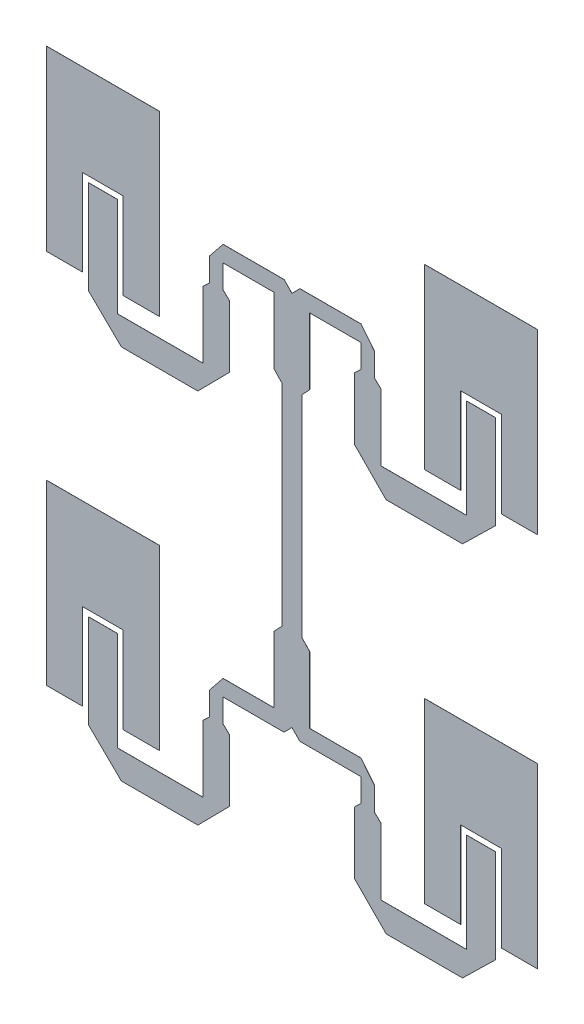
SolidWorks part; units mm, degrees
material "Медь"
ref_plane "Спереди" through (0, 0, 0) normal (0, 0, 1) x (1, 0, 0)
ref_plane "Сверху" through (0, 0, 0) normal (0, 1, 0) x (1, 0, 0)
ref_plane "Справа" through (0, 0, 0) normal (1, 0, 0) x (0, 0, -1)
sketch "Patch1" plane through (0, 0, 0) normal (0, 0, 1) x (1, 0, 0)
  line L0 (0, 0) -> (0, 64.0927) construction
  line L1 (-59.6963, 67.2973) -> (-32.2263, 67.2973)
  line L2 (-59.6963, 67.2973) -> (-59.6964, 24.0919)
  line L3 (-59.6964, 24.0919) -> (-50.8953, 24.0919)
  line L4 (-32.2263, 67.2973) -> (-32.2263, 24.0919)
  line L5 (-59.6963, 67.2973) -> (-32.2263, 24.0919) construction
  line L6 (-59.6964, 24.0919) -> (-32.2263, 67.2973) construction
  line L7 (-45.9613, 45.6946) -> (-45.9613, 25.1206) construction
  line L8 (45.9613, 45.6946) -> (45.9613, 25.1206) construction
  line L9 (-50.8953, 24.0919) -> (-50.8952, 45.0723)
  line L10 (-50.8952, 45.0723) -> (-41.0273, 45.0723)
  line L11 (-41.0273, 24.0919) -> (-41.0273, 45.0723)
  line L12 (-41.0273, 24.0919) -> (-32.2263, 24.0919)
  line L13 (59.6964, 24.0919) -> (32.2263, 67.2973) construction
  line L14 (59.6963, 67.2973) -> (32.2263, 24.0919) construction
  line L15 (41.0273, 24.0919) -> (32.2263, 24.0919)
  line L16 (41.0273, 24.0919) -> (41.0273, 45.0723)
  line L17 (50.8952, 45.0723) -> (41.0273, 45.0723)
  line L18 (50.8953, 24.0919) -> (50.8952, 45.0723)
  line L19 (32.2263, 67.2973) -> (32.2263, 24.0919)
  line L20 (59.6964, 24.0919) -> (50.8953, 24.0919)
  line L21 (59.6963, 67.2973) -> (59.6964, 24.0919)
  line L22 (59.6963, 67.2973) -> (32.2263, 67.2973)
  line L23 (-41.0274, -67.2973) -> (-32.2263, -67.2973)
  line L24 (-32.2263, -24.0919) -> (-32.2263, -67.2973)
  line L25 (-59.6964, -24.0919) -> (-32.2263, -24.0919)
  line L26 (-59.6964, -24.0919) -> (-32.2263, -67.2973) construction
  line L27 (-50.8953, -46.3169) -> (-41.0274, -46.3169)
  line L28 (-59.6964, -24.0919) -> (-59.6964, -67.2973)
  line L29 (-50.8953, -67.2973) -> (-50.8953, -46.3169)
  line L30 (-59.6964, -67.2973) -> (-32.2263, -24.0919) construction
  line L31 (-41.0274, -67.2973) -> (-41.0274, -46.3169)
  line L32 (-59.6964, -67.2973) -> (-50.8953, -67.2973)
  line L33 (-45.9613, -45.6946) -> (-45.9613, -66.2686) construction
  line L34 (45.9613, -45.6946) -> (45.9613, -66.2686) construction
  line L35 (59.6964, -67.2973) -> (32.2263, -24.0919) construction
  line L36 (59.6964, -24.0919) -> (32.2263, -67.2973) construction
  line L37 (59.6964, -67.2973) -> (50.8953, -67.2973)
  line L38 (41.0274, -67.2973) -> (41.0274, -46.3169)
  line L39 (50.8953, -67.2973) -> (50.8953, -46.3169)
  line L40 (59.6964, -24.0919) -> (59.6964, -67.2973)
  line L41 (50.8953, -46.3169) -> (41.0274, -46.3169)
  line L42 (59.6964, -24.0919) -> (32.2263, -24.0919)
  line L43 (32.2263, -24.0919) -> (32.2263, -67.2973)
  line L44 (41.0274, -67.2973) -> (32.2263, -67.2973)
  point P0 (-45.9613, 45.6946)
  point P24 (-45.9613, -45.6946)
  dimension "D1" = 43.2054
  dimension "D2" = 27.4701
  dimension "D3" = 45.9613
  dimension "D5" = 20.9804
  dimension "D6" = 8.8011
  dimension "D4" = 45.6946
  dimension "D7" = 43.2054
  dimension "D8" = 27.4701
  dimension "D9" = 20.9804
  dimension "D10" = 8.8011
  dimension "D11" = 45.9613
  dimension "D12" = 45.6946
sketch "Feed1" plane through (0, 0, 0) normal (0, 0, 1) x (1, 0, 0)
  line L0 (-50.8952, 45.0723) -> (-41.0273, 45.0723) construction
  line L1 (-49.4729, 43.6499) -> (-42.4498, 43.6499)
  line L2 (-49.4729, 43.6499) -> (-49.4729, 20.8915)
  line L3 (-49.4729, 20.8915) -> (-41.4719, 13.0683)
  line L4 (-42.4498, 43.6499) -> (-42.4498, 19.558)
  line L5 (-50.8953, 24.0919) -> (-50.8953, 45.0723) construction
  line L6 (-15.1575, 20.8915) -> (-22.8918, 13.0683)
  line L7 (-21.6472, 35.7378) -> (-20.047, 37.2491)
  line L8 (15.1574, -70.4977) -> (15.1574, -55.4736)
  line L9 (-41.4719, 13.0683) -> (-22.8918, 13.0683)
  line L10 (-21.6472, 19.558) -> (-21.6472, 35.7378)
  line L11 (1.9114, 47.0281) -> (0, 45.0723)
  line L12 (42.4498, -71.8312) -> (21.6471, -71.8312)
  line L13 (-20.047, 42.9387) -> (-20.047, 37.2491)
  line L14 (41.4718, -78.3209) -> (22.8917, -78.3209)
  line L15 (-42.4498, 19.558) -> (-21.6472, 19.558)
  line L16 (-15.1574, -70.4977) -> (-22.8917, -78.3209)
  line L17 (-20.047, 42.9387) -> (-16.7577, 47.0281)
  line L18 (-15.1575, 20.8915) -> (-15.1575, 35.9156)
  line L19 (-16.7577, 43.1165) -> (-4.3117, 43.1165)
  line L20 (-16.7577, 43.1165) -> (-16.7577, 37.4269)
  line L21 (-16.7577, 37.4269) -> (-15.1575, 35.9156)
  line L22 (0, 0) -> (0, 64.0927) construction
  line L23 (-16.7577, 47.0281) -> (-1.9114, 47.0281)
  line L24 (-21.6471, -55.6514) -> (-20.0469, -54.1401)
  line L25 (-16.7576, -48.2727) -> (-1.9114, -48.2727)
  line L26 (-1.9114, 47.0281) -> (0, 45.0723)
  line L27 (16.7577, 47.0281) -> (1.9114, 47.0281)
  line L28 (16.7577, 37.4269) -> (15.1575, 35.9156)
  line L29 (16.7577, 43.1165) -> (16.7577, 37.4269)
  line L30 (16.7577, 43.1165) -> (4.3117, 43.1165)
  line L31 (15.1575, 20.8915) -> (15.1575, 35.9156)
  line L32 (20.047, 42.9387) -> (16.7577, 47.0281)
  line L33 (-21.6471, -71.8312) -> (-21.6471, -55.6514)
  line L34 (42.4498, 19.558) -> (21.6472, 19.558)
  line L35 (-20.047, -48.4505) -> (-16.7577, -44.3611)
  line L36 (20.047, 42.9387) -> (20.047, 37.2491)
  line L37 (-49.4729, -47.7393) -> (-42.4498, -47.7393)
  line L38 (21.6472, 19.558) -> (21.6472, 35.7378)
  line L39 (41.4719, 13.0683) -> (22.8918, 13.0683)
  line L40 (21.6472, 35.7378) -> (20.047, 37.2491)
  line L41 (15.1575, 20.8915) -> (22.8918, 13.0683)
  line L42 (42.4498, 43.6499) -> (42.4498, 19.558)
  line L43 (49.4729, 20.8915) -> (41.4719, 13.0683)
  line L44 (49.4729, 43.6499) -> (49.4729, 20.8915)
  line L45 (49.4729, 43.6499) -> (42.4498, 43.6499)
  line L46 (-49.4729, -70.4977) -> (-41.4718, -78.3209)
  line L47 (20.047, -48.4505) -> (20.0469, -54.1401)
  line L48 (15.1574, -70.4977) -> (22.8917, -78.3209)
  line L49 (42.4498, -47.7393) -> (42.4498, -71.8312)
  line L50 (49.4729, -47.7393) -> (49.4729, -70.4977)
  line L51 (-4.3117, 26.9367) -> (-4.3117, 43.1165)
  line L52 (16.7576, -53.9623) -> (15.1574, -55.4736)
  line L53 (-42.4498, -47.7393) -> (-42.4498, -71.8312)
  line L54 (16.7577, -44.3611) -> (4.3117, -44.3611)
  line L55 (16.7576, -48.2727) -> (16.7576, -53.9623)
  line L56 (21.6471, -55.6514) -> (20.0469, -54.1401)
  line L57 (49.4729, -47.7393) -> (42.4498, -47.7393)
  line L58 (-49.4729, -47.7393) -> (-49.4729, -70.4977)
  line L59 (-16.7576, -53.9623) -> (-15.1574, -55.4736)
  line L60 (21.6471, -71.8312) -> (21.6471, -55.6514)
  line L61 (-42.4498, -71.8312) -> (-21.6471, -71.8312)
  line L62 (-16.7577, -44.3611) -> (-4.3117, -44.3611)
  line L63 (-41.4718, -78.3209) -> (-22.8917, -78.3209)
  line L64 (-16.7576, -48.2727) -> (-16.7576, -53.9623)
  line L65 (-15.1574, -70.4977) -> (-15.1574, -55.4736)
  line L66 (16.7576, -48.2727) -> (1.9114, -48.2727)
  line L67 (0, -86.952) -> (0, -22.8593) construction
  line L68 (49.4729, -70.4977) -> (41.4718, -78.3209)
  line L69 (4.3117, 26.9367) -> (4.3117, 43.1165)
  line L70 (-20.047, -48.4505) -> (-20.0469, -54.1401)
  line L71 (20.047, -48.4505) -> (16.7577, -44.3611)
  line L72 (-1.9114, -48.2727) -> (0, -46.3169)
  line L73 (1.9114, -48.2727) -> (0, -46.3169)
  line L74 (-4.3117, -44.3611) -> (-4.3117, -28.1813)
  line L75 (4.3117, -44.3611) -> (4.3117, -28.1813)
  line L76 (-2.4447, 24.9809) -> (-4.3117, 26.9367)
  line L77 (-50.8953, -46.3169) -> (-41.0274, -46.3169) construction
  line L78 (-41.0274, -67.2973) -> (-41.0274, -46.3169) construction
  line L79 (-4.3117, -28.1813) -> (-2.4447, -26.2255)
  line L80 (4.3117, -28.1813) -> (2.4447, -26.2255)
  line L81 (-2.4447, -26.2255) -> (-2.4447, 24.9809)
  line L82 (2.4447, -26.2255) -> (2.4447, 24.9809)
  line L83 (2.4447, 24.9809) -> (4.3117, 26.9367)
  dimension "D1" = 1.4224
  dimension "D2" = 1.4224
  dimension "D5" = 7.8232
  dimension "D6" = 8.001
  dimension "D7" = 22.7584
  dimension "D8" = 18.5801
  dimension "D11" = 7.7343
  dimension "D13" = 15.0241
  dimension "D14" = 3.2893
  dimension "D16" = 1.5113
  dimension "D17" = 1.6002
  dimension "D15" = 5.6896
  dimension "D18" = 1.5113
  dimension "D19" = 7.8232
  dimension "D23" = 5.6896
  dimension "D21" = 3.2893
  dimension "D22" = 3.9116
  dimension "D25" = 1.9558
  dimension "D24" = 14.8463
  dimension "D20" = 1.9114
  dimension "D10" = 16.1798
  dimension "D12" = 6.4897
  dimension "D9" = 6.4897
  dimension "D3" = 1.4224
  dimension "D4" = 7.8232
  dimension "D27" = 8.001
  dimension "D28" = 22.7584
  dimension "D29" = 18.5801
  dimension "D30" = 7.7343
  dimension "D31" = 15.0241
  dimension "D32" = 3.2893
  dimension "D33" = 1.5113
  dimension "D34" = 1.6002
  dimension "D35" = 5.6896
  dimension "D36" = 1.5113
  dimension "D37" = 7.8232
  dimension "D38" = 5.6896
  dimension "D39" = 3.2893
  dimension "D40" = 3.9116
  dimension "D45" = 16.1798
  dimension "D46" = 6.4897
  dimension "D47" = 6.4897
  dimension "D41" = 1.9558
  dimension "D42" = 4.3117
  dimension "D43" = 4.3117
  dimension "D44" = 1.4224
  dimension "D48" = 1.4224
  dimension "D49" = 1.4224
  dimension "D50" = 1.4224
  dimension "D51" = 16.1798
  dimension "D52" = 4.8895
  dimension "D53" = 1.9558
  dimension "D54" = 1.9558
  dimension "D56" = 4.3117
  dimension "D26" = 16.1798
  dimension "D55" = 8.6233
  dimension "D57" = 16.1798
  dimension "D58" = 8.6233
  dimension "D59" = 1.9558
  dimension "D60" = 1.9558
  dimension "D61" = 4.8895
  dimension "D62" = 1.9558
  dimension "D63" = 1.9114
  dimension "D64" = 1.9114
  dimension "D65" = 2.4447
  dimension "D66" = 4.3117
  dimension "D67" = 2.4447
  dimension "D68" = 2.4447
  dimension "D69" = 4.3117
extrude "Feed" add sketch "Feed1" along normal blind 0.018
extrude "Patch" add sketch "Patch1" along normal blind 0.018 separate body
equation "\"dpi\"= ( 25.4 / 300 ) * 1.05"
equation "\"D2@Patch1\" = \"patch_w\""
equation "\"D1@Patch1\" = \"patch_h\""
equation "\"D3@Patch1\" = \"patch_pos_hor\""
equation "\"D6@Patch1\" = \"patch_border_w\""
equation "\"D5@Patch1\" = \"patch_border_h\""
equation "\"D4@Patch1\" = \"patch_pos_vert\""
equation "\"patch_w\"= 309 * \"dpi\""
equation "\"patch_h\"= 486 * \"dpi\""
equation "\"patch_border_w\"= 99 * \"dpi\""
equation "\"patch_pos_hor\"= 517 * \"dpi\""
equation "\"patch_border_h\"= 236 * \"dpi\""
equation "\"patch_pos_vert\"= 514 * \"dpi\""
equation "\"D10@Patch1\" = \"patch_border_w\""
equation "\"D8@Patch1\" = \"patch_w\""
equation "\"D11@Patch1\" = \"patch_pos_hor\""
equation "\"D12@Patch1\" = \"patch_pos_vert\""
equation "\"D7@Patch1\" = \"patch_h\""
equation "\"D9@Patch1\" = \"patch_border_h\""
equation "\"mstrp_border\"= 16 * \"dpi\""
equation "\"D1@Feed1\" = \"mstrp_border\""
equation "\"D2@Feed1\" = \"mstrp_border\""
equation "\"D3@Feed1\" = \"mstrp_border\""
equation "\"mstrp_1h\"= 256 * \"dpi\""
equation "\"D5@Feed1\" = 88 * \"dpi\""
equation "\"D6@Feed1\" = 90 * \"dpi\""
equation "\"D7@Feed1\"=\"mstrp_1h\""
equation "\"mstrp_2h\"= 73 * \"dpi\""
equation "\"mstrp_2w\"= 209 * \"dpi\""
equation "\"D8@Feed1\" = \"mstrp_2w\""
equation "\"D9@Feed1\" = \"mstrp_2h\""
equation "\"D10@Feed1\" = 182 * \"dpi\""
equation "\"D11@Feed1\" = 87 * \"dpi\""
equation "\"D12@Feed1\"=73 * \"dpi\""
equation "\"D13@Feed1\" = 169 * \"dpi\""
equation "\"D14@Feed1\" = 37 * \"dpi\""
equation "\"D15@Feed1\" = 64 * \"dpi\""
equation "\"D16@Feed1\"=17 * \"dpi\""
equation "\"D17@Feed1\" = 18 * \"dpi\""
equation "\"D18@Feed1\" = 17 * \"dpi\""
equation "\"D19@Feed1\" = 88 * \"dpi\""
equation "\"D20@Feed1\" = 21.5 * \"dpi\""
equation "\"D21@Feed1\" = 37 * \"dpi\""
equation "\"D22@Feed1\" = 44 * \"dpi\""
equation "\"D24@Feed1\" = 167 * \"dpi\""
equation "\"D25@Feed1\" = 22 * \"dpi\""
equation "\"D26@Feed1\" = 182 * \"dpi\""
equation "\"D23@Feed1\" = 64 * \"dpi\""
equation "\"D41@Feed1\" = 22 * \"dpi\""
equation "\"D42@Feed1\" =  ( 97 / 2 )  * \"dpi\""
equation "\"D43@Feed1\" = 97 / 2 * \"dpi\""
equation "\"D44@Feed1\" = \"mstrp_border\""
equation "\"D48@Feed1\" = \"mstrp_border\""
equation "\"D49@Feed1\" = \"mstrp_border\""
equation "\"D50@Feed1\" = \"mstrp_border\""
equation "\"D51@Feed1\" = 182 * \"dpi\""
equation "\"D53@Feed1\" = 22 * \"dpi\""
equation "\"D54@Feed1\" = 22 * \"dpi\""
equation "\"D52@Feed1\" = 55 * \"dpi\""
equation "\"D55@Feed1\" = 97 * \"dpi\""
equation "\"D56@Feed1\" = 97 / 2 * \"dpi\""
equation "\"D57@Feed1\" = 182 * \"dpi\""
equation "\"D58@Feed1\" = 97 * \"dpi\""
equation "\"D59@Feed1\" = 22 * \"dpi\""
equation "\"D60@Feed1\" = 22 * \"dpi\""
equation "\"D61@Feed1\" = 55 * \"dpi\""
equation "\"D28@Feed1\"=\"mstrp_1h\""
equation "\"D27@Feed1\"=90 * \"dpi\""
equation "\"D46@Feed1\"=73 * \"dpi\""
equation "\"D45@Feed1\"=182 * \"dpi\""
equation "\"D33@Feed1\"=17 * \"dpi\""
equation "\"D4@Feed1\"=88 * \"dpi\""
equation "\"D37@Feed1\"=88 * \"dpi\""
equation "\"D47@Feed1\"=\"mstrp_2h\""
equation "\"D29@Feed1\"=\"mstrp_2w\""
equation "\"D31@Feed1\"=169 * \"dpi\""
equation "\"D34@Feed1\"=18 * \"dpi\""
equation "\"D35@Feed1\"=64 * \"dpi\""
equation "\"D39@Feed1\"=37 * \"dpi\""
equation "\"D32@Feed1\"=37 * \"dpi\""
equation "\"D40@Feed1\"=44 * \"dpi\""
equation "\"D36@Feed1\"=17 * \"dpi\""
equation "\"D38@Feed1\"=64 * \"dpi\""
equation "\"D30@Feed1\"=87 * \"dpi\""
equation "\"D62@Feed1\"=22 * \"dpi\""
equation "\"D63@Feed1\"=21.5 * \"dpi\""
equation "\"D64@Feed1\"=21.5 * \"dpi\""
equation "\"D65@Feed1\"=27.5*\"dpi\""
equation "\"D66@Feed1\"=97/2*\"dpi\""
equation "\"D67@Feed1\"=27.5*\"dpi\""
equation "\"D68@Feed1\"=27.5*\"dpi\""
equation "\"D69@Feed1\"=97/2*\"dpi\""
